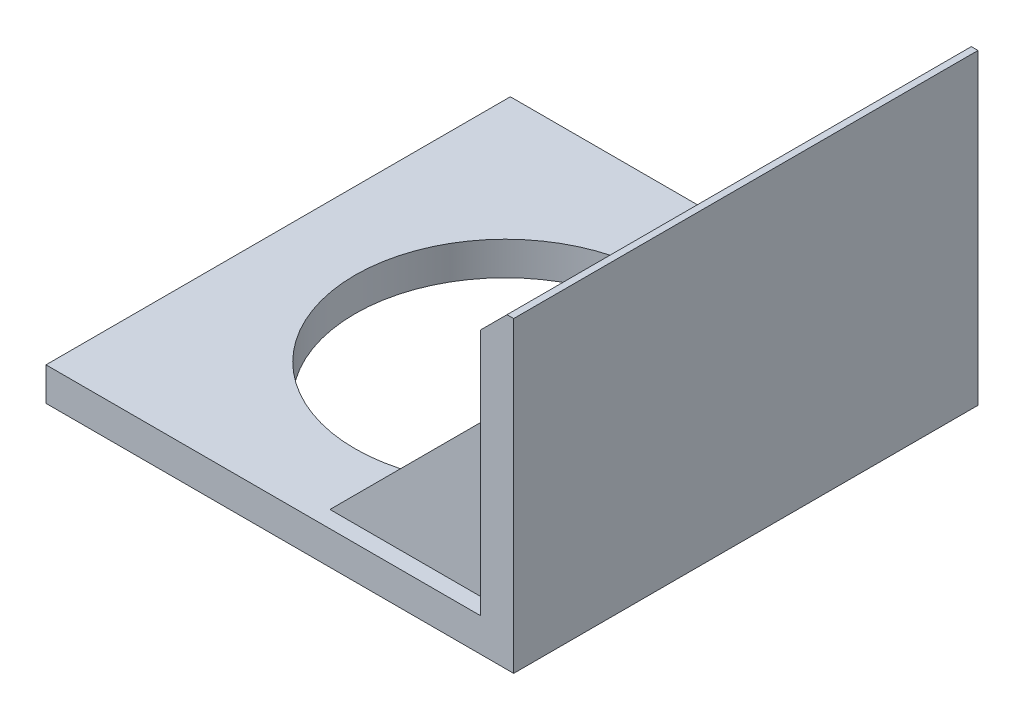
SolidWorks part; units mm, degrees
material "C40 or 38NiCrMo4"
ref_plane "Piano frontale" through (0, 0, 0) normal (0, 0, 1) x (1, 0, 0)
ref_plane "Piano superiore" through (0, 0, 0) normal (0, 1, 0) x (1, 0, 0)
ref_plane "Piano destro" through (0, 0, 0) normal (1, 0, 0) x (0, 0, -1)
sketch "Sketch1" plane through (0, 0, 0) normal (0, 1, 0) x (1, 0, 0)
  line L0 (-1000, 0) -> (49000, 0) construction
  line L1 (0, -1000) -> (0, 49000) construction
  line L2 (0, 69.5) -> (-68, 69.5)
  line L3 (-68, 69.5) -> (-68, -69.5)
  line L4 (0, -69.5) -> (-68, -69.5)
  line L5 (0, 69.5) -> (72, 69.5)
  line L6 (72, 69.5) -> (72, -69.5)
  line L7 (0, -69.5) -> (72, -69.5)
  circle A0 centre (0, 0) radius 45
  point P11 (-68, 0)
  point P15 (72, 0)
  dimension "D1" = 90
  dimension "D2" = 69.5
  dimension "D3" = 68
  dimension "D4" = 72
extrude "Extrude1" add sketch "Sketch1" along normal blind 10
sketch "Sketch2" plane through (0, 10, 0) normal (0, 1, 0) x (1, 0, 0)
  line L1 (72, 69.5) -> (62, 69.5)
  line L2 (72, 69.5) -> (72, -69.5)
  line L3 (72, -69.5) -> (62, -69.5)
  line L4 (62, 69.5) -> (62, -69.5)
  line L5 (-68, -69.5) -> (72, -69.5) construction
  dimension "D1" = 139
  dimension "D2" = 10
extrude "Extrude2" add sketch "Sketch2" along normal blind 82
chamfer "Chamfer1" distance 8 angle 45 1 edges at (62, 92, 0)
sketch "Sketch3" plane through (0, 0, 69.5) normal (0, 0, 1) x (1, 0, 0)
  line L0 (12, 10) -> (62, 10)
  line L1 (-68, 10) -> (62, 10) construction
  line L2 (62, 10) -> (62, 60)
  line L3 (62, 84) -> (62, 10) construction
  line L4 (62, 60) -> (12, 10)
  dimension "D1" = 50
  dimension "D2" = 50
extrude "Extrude3" add sketch "Sketch3" against normal blind 8 from offset 5 offset against normal yes
pattern_linear "LPattern1" count 2 spacing 121 along (0, 0, -1) of "Extrude3"
